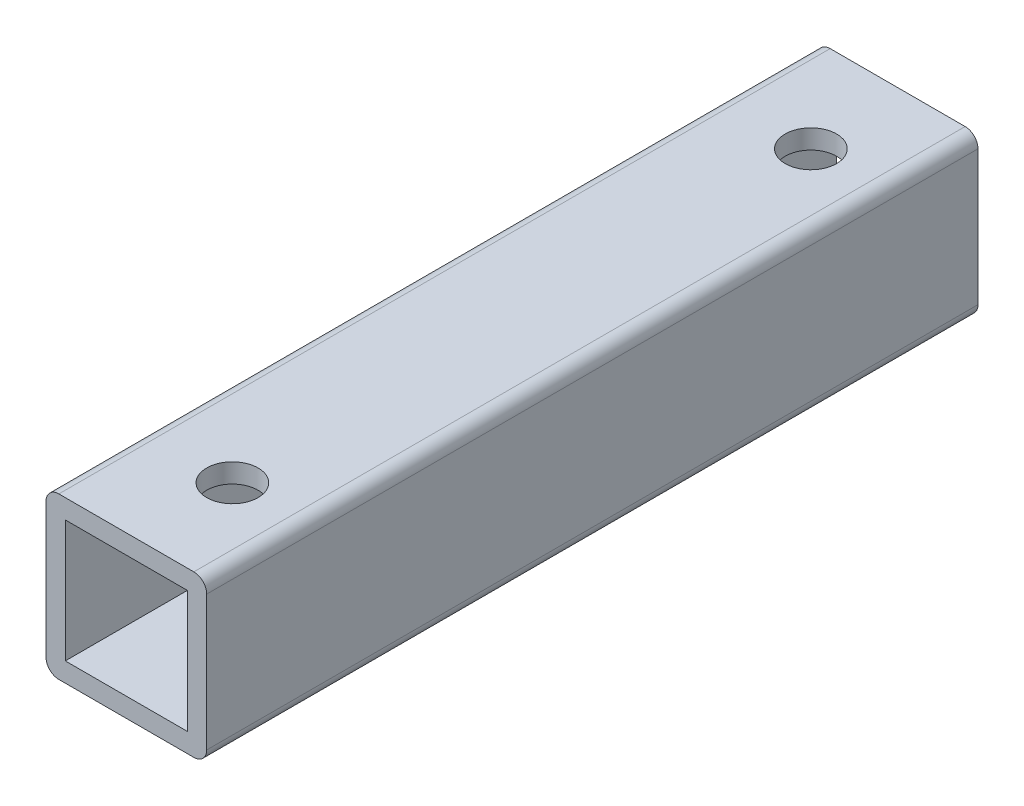
SolidWorks part; units mm, degrees
ref_plane "Front" through (0, 0, 0) normal (0, 0, 1) x (1, 0, 0)
ref_plane "Top" through (0, 0, 0) normal (0, 1, 0) x (1, 0, 0)
ref_plane "Right" through (0, 0, 0) normal (1, 0, 0) x (0, 0, -1)
sketch "Sketch1" plane through (0, 0, 0) normal (0, 0, 1) x (1, 0, 0)
  line L1 (-12.5, -12.5) -> (12.5, -12.5)
  line L2 (-12.5, -12.5) -> (-12.5, 12.5)
  line L3 (-12.5, 12.5) -> (12.5, 12.5)
  line L4 (12.5, -12.5) -> (12.5, 12.5)
  line L5 (-12.5, -12.5) -> (12.5, 12.5) construction
  line L6 (-12.5, 12.5) -> (12.5, -12.5) construction
  point P0 (0, 0)
  dimension "D1" = 25
  dimension "D2" = 25
extrude "Extrude-Thin1" add sketch "Sketch1" along normal blind 60 and the other way blind 60 thin thin type one direction reverse wall 3
fillet "Fillet1" radius 2 4 edges at (-12.5, -12.5, 0) (12.5, -12.5, 0) (-12.5, 12.5, 0) (12.5, 12.5, 0)
sketch "Sketch3" plane through (0, 12.5, 0) normal (0, 1, 0) x (1, 0, 0)
  line L0 (12.5, 60) -> (12.5, -60) construction
  line L1 (12.5, -60) -> (12.5, 60) construction
  line L2 (10.5, 60) -> (-10.5, 60) construction
  line L4 (10.5, -60) -> (-10.5, -60) construction
  circle A0 centre (1.5, -45) radius 4
  circle A1 centre (1.5, 45) radius 4
  dimension "D1" = 8
  dimension "D2" = 8
  dimension "D3" = 15
  dimension "D4" = 15
  dimension "D5" = 11
  dimension "D6" = 11
extrude "Cut-Extrude2" cut sketch "Sketch3" against normal through all
